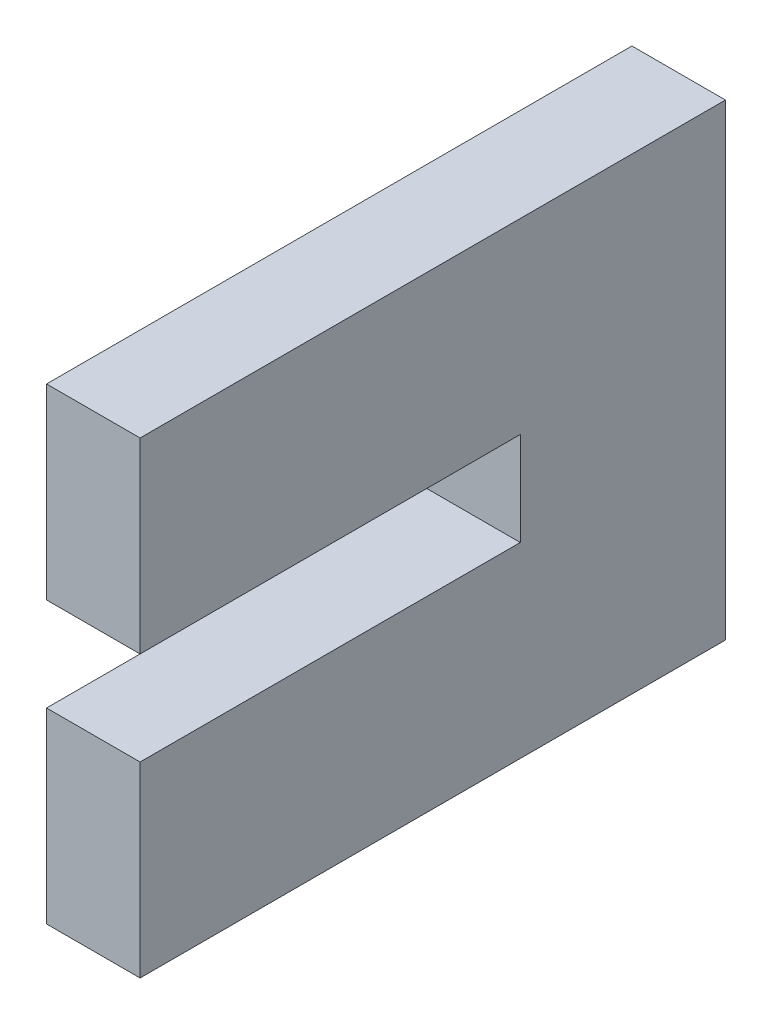
SolidWorks part; units mm, degrees
ref_plane "Front Plane" through (0, 0, 0) normal (0, 0, 1) x (1, 0, 0)
ref_plane "Top Plane" through (0, 0, 0) normal (0, 1, 0) x (1, 0, 0)
ref_plane "Right Plane" through (0, 0, 0) normal (1, 0, 0) x (0, 0, -1)
sketch "Sketch1" plane through (0, 0, 0) normal (1, 0, 0) x (0, 0, -1)
  line L0 (36.2581, 20) -> (36.2581, -20)
  line L1 (36.2581, -20) -> (-13.8065, -20)
  line L2 (-13.8065, -20) -> (-13.8065, -4)
  line L3 (-13.8065, -4) -> (18.7097, -4)
  line L4 (18.7097, -4) -> (18.7097, 4)
  line L5 (18.7097, 4) -> (-13.8065, 4)
  line L6 (-13.8065, 4) -> (-13.8065, 20)
  line L7 (-13.8065, 20) -> (36.2581, 20)
  point P2 (36.2581, 0)
  dimension "D1" = 8
  dimension "D2" = 40
extrude "Boss-Extrude1" add sketch "Sketch1" along normal mid plane 8
